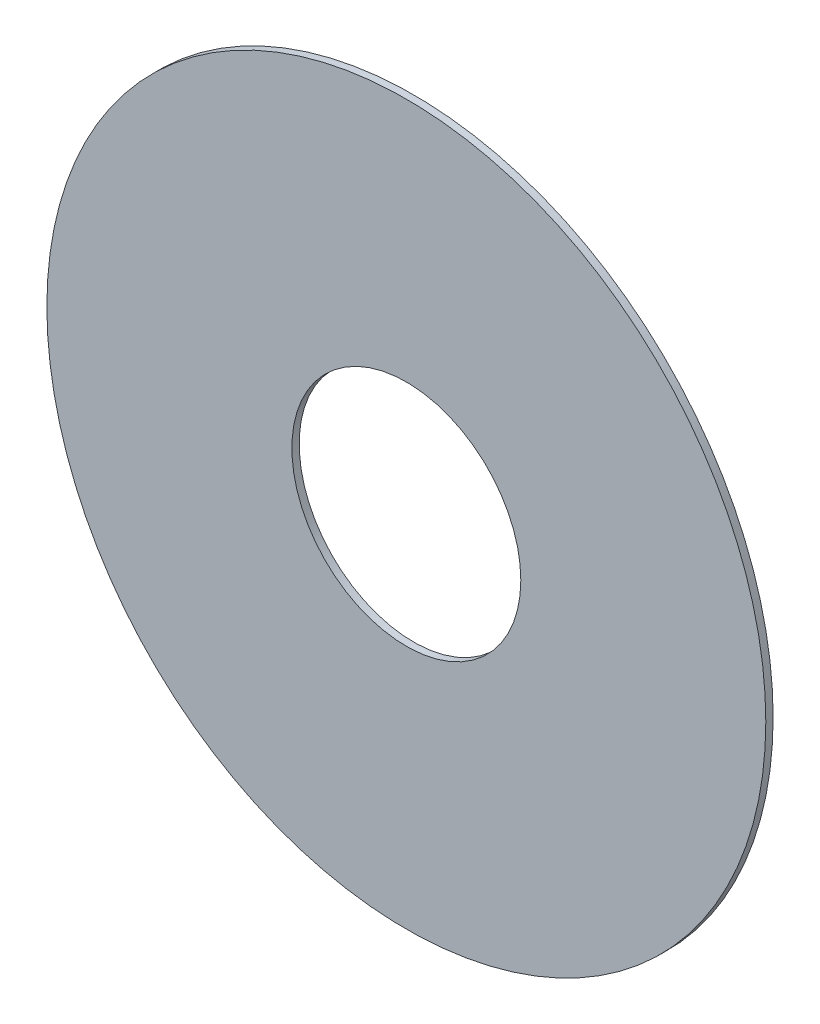
SolidWorks part; units mm, degrees
ref_plane "Primary" through (0, 0, 0) normal (0, 0, 1) x (1, 0, 0)
ref_plane "Top" through (0, 0, 0) normal (0, 1, 0) x (1, 0, 0)
ref_plane "Side" through (0, 0, 0) normal (1, 0, 0) x (0, 0, -1)
sketch "Sketch1" plane through (0, 0, 0) normal (0, 0, 1) x (1, 0, 0)
  circle A0 centre (0, 0) radius 99.695
  circle A1 centre (0, 0) radius 31.75
  dimension "D1" = 63.5
  dimension "D2" = 199.39
extrude "Base-Extrude" add sketch "Sketch1" along normal blind 2.032
